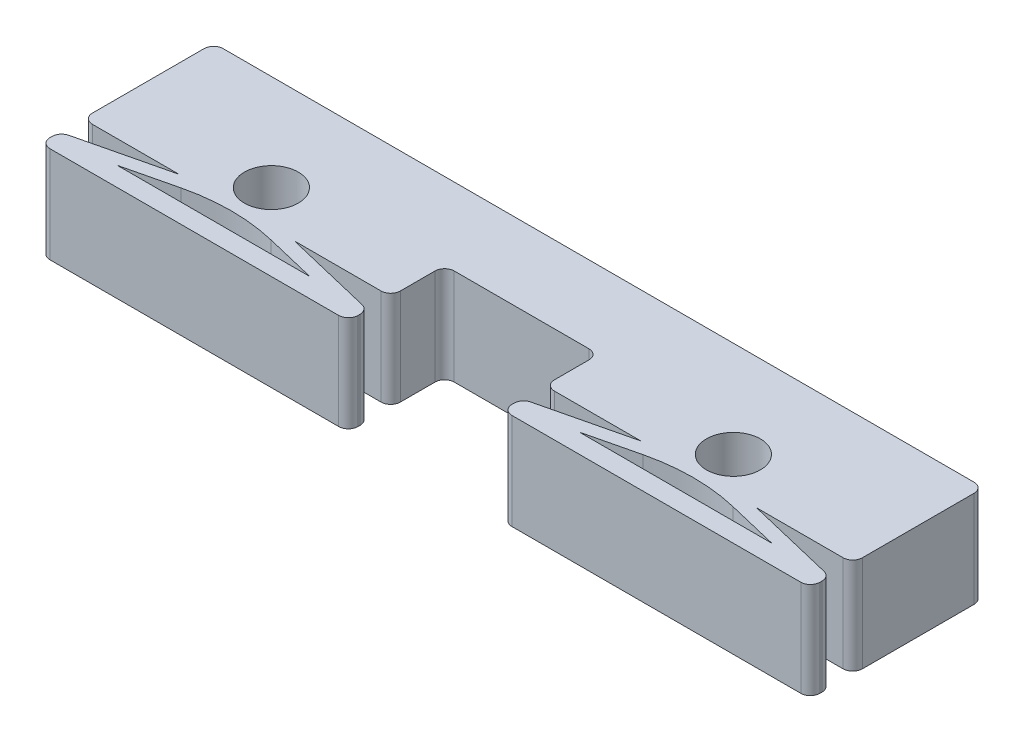
SolidWorks part; units mm, degrees
ref_plane "Front Plane" through (0, 0, 0) normal (0, 0, 1) x (1, 0, 0)
ref_plane "Top Plane" through (0, 0, 0) normal (0, 1, 0) x (1, 0, 0)
ref_plane "Right Plane" through (0, 0, 0) normal (1, 0, 0) x (0, 0, -1)
sketch "Sketch1" plane through (0, 0, 0) normal (0, 1, 0) x (1, 0, 0)
  line L0 (0, 0) -> (0, 9)
  line L1 (0, 9) -> (40, 9)
  line L2 (40, 9) -> (40, 0)
  line L3 (0, 0) -> (16, 0)
  line L4 (16, 0) -> (16, 5)
  line L5 (16, 5) -> (24, 5)
  line L6 (24, 5) -> (24, 0)
  line L7 (24, 0) -> (40, 0)
  dimension "D1" = 40
  dimension "D2" = 9
  dimension "D3" = 9
  dimension "D4" = 16
  dimension "D5" = 16
  dimension "D6" = 5
extrude "Boss-Extrude1" add sketch "Sketch1" along normal blind 5
sketch "Sketch2" plane through (0, 5, 0) normal (0, 1, 0) x (1, 0, 0)
  line L0 (0, 9) -> (8, 9)
  line L1 (40, 9) -> (0, 9) construction
  line L2 (8, 9) -> (8, 4)
  line L3 (8, 4) -> (32, 4)
  line L4 (0, 0) -> (0, 2.2) construction
  line L5 (0, 9) -> (0, 0) construction
  line L6 (0, 2.2) -> (19.4811, 2.2) construction
  line L7 (0, 2.2) -> (5, 2.2)
  line L8 (5, 2.2) -> (8, 2.2)
  line L9 (0, 0) -> (0, 1)
  line L10 (5, 2.2) -> (0, 1)
  line L11 (0, 1) -> (0, 2.2)
  line L12 (0, 1) -> (3, 1)
  line L13 (3, 1) -> (8, 2.2)
  line L14 (0, 1) -> (12.9505, 1) construction
  line L15 (16, 1) -> (13, 1)
  line L16 (16, 0) -> (16, 5) construction
  line L17 (8, 2.2) -> (11, 2.2)
  line L18 (8, 2.2) -> (13, 1)
  line L19 (11, 2.2) -> (16, 1)
  line L20 (24, 1) -> (27, 1)
  line L21 (24, 5) -> (24, 0) construction
  line L22 (40, 2.2) -> (35, 2.2)
  line L23 (40, 0) -> (40, 9) construction
  line L24 (35, 2.2) -> (32, 2.2)
  line L25 (32, 2.2) -> (29, 2.2)
  line L26 (24, 1) -> (29, 2.2)
  line L27 (27, 1) -> (32, 2.2)
  line L28 (40, 1) -> (37, 1)
  line L29 (32, 2.2) -> (37, 1)
  line L30 (35, 2.2) -> (40, 1)
  line L31 (3, 1) -> (13, 1)
  line L32 (11, 2.2) -> (16, 2.2)
  line L33 (16, 2.2) -> (16, 1)
  line L34 (24, 1) -> (24, 2.2)
  line L35 (24, 2.2) -> (29, 2.2)
  line L36 (27, 1) -> (37, 1)
  line L37 (40, 1) -> (40, 2.2)
  circle A0 centre (8, 4) radius 1.4
  circle A1 centre (32, 4) radius 1.4
  dimension "D2" = 2.8
  dimension "D4" = 2.8
  dimension "D1" = 8
  dimension "D3" = 24
  dimension "D5" = 5
  dimension "D6" = 2.2
  dimension "D7" = 1
  dimension "D8" = 5
  dimension "D9" = 3
  dimension "D10" = 3
  dimension "D11" = 3
  dimension "D12" = 3
  dimension "D13" = 3
  dimension "D14" = 5
  dimension "D15" = 3
  dimension "D16" = 3
  dimension "D17" = 3
extrude "Cut-Extrude1" cut sketch "Sketch2" along normal blind 5 and the other way blind 10
fillet "Fillet1" radius 10 2 edges at (32, 2.5, -2.2) (8, 2.5, -2.2)
fillet "Fillet2" radius 0.5 16 edges at (40, 2.5, -9) (0, 2.5, -9) (0, 2.5, -2.2) (0, 2.5, -1) (0, 2.5, 0) (24, 2.5, -5) (16, 2.5, -5) (16, 2.5, -1) (16, 2.5, 0) (16, 2.5, -2.2) (24, 2.5, -2.2) (24, 2.5, -1) (24, 2.5, 0) (40, 2.5, 0) (40, 2.5, -1) (40, 2.5, -2.2)
